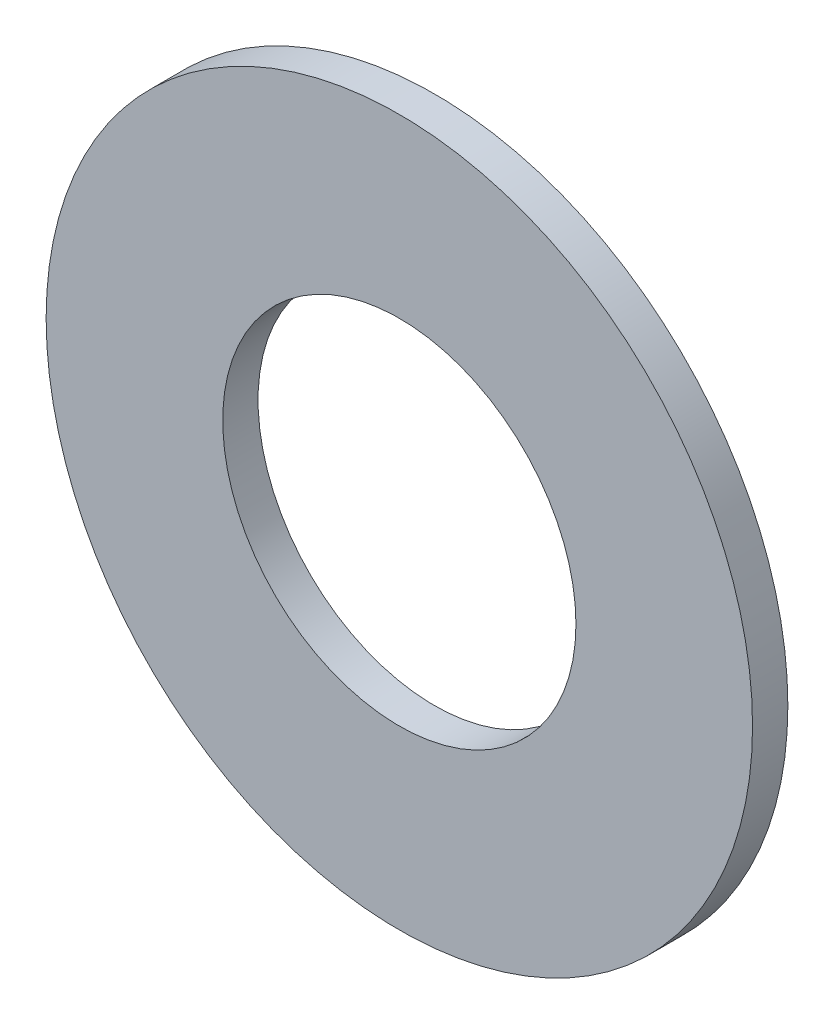
SolidWorks part; units mm, degrees
ref_plane "Front Plane" through (0, 0, 0) normal (0, 0, 1) x (1, 0, 0)
ref_plane "Top Plane" through (0, 0, 0) normal (0, 1, 0) x (1, 0, 0)
ref_plane "Right Plane" through (0, 0, 0) normal (1, 0, 0) x (0, 0, -1)
sketch "Sketch1" plane through (0, 0, 0) normal (0, 0, 1) x (1, 0, 0)
  circle A0 centre (0, 0) radius 3
  circle A1 centre (0, 0) radius 1.5
  dimension "D1" = 6
  dimension "D2" = 3
extrude "Boss-Extrude1" add sketch "Sketch1" along normal blind 0.3
